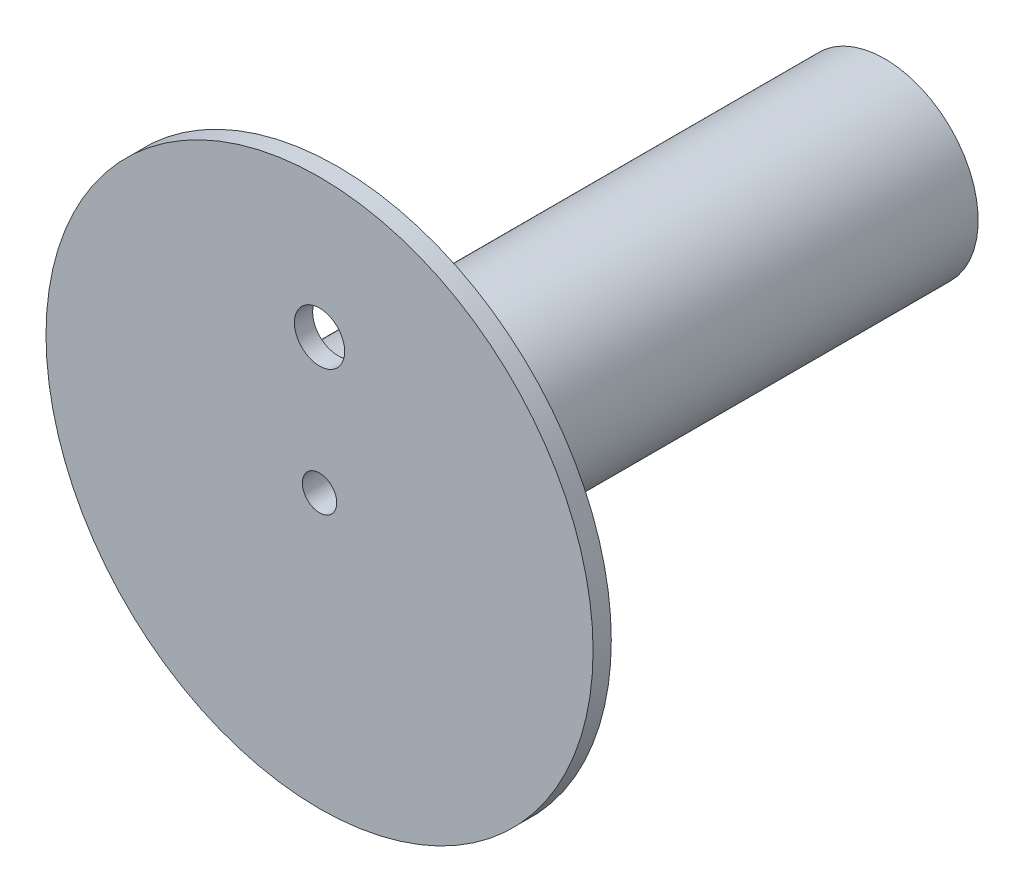
SolidWorks part; units mm, degrees
ref_plane "Front Plane" through (0, 0, 0) normal (0, 0, 1) x (1, 0, 0)
ref_plane "Top Plane" through (0, 0, 0) normal (0, 1, 0) x (1, 0, 0)
ref_plane "Right Plane" through (0, 0, 0) normal (1, 0, 0) x (0, 0, -1)
sketch "Sketch1" plane through (0, 0, 0) normal (0, 0, 1) x (1, 0, 0)
  circle A0 centre (0, 0) radius 6.5
  dimension "D1" = 13
extrude "Boss-Extrude1" add sketch "Sketch1" along normal blind 38.1
sketch "Sketch2" plane through (0, 0, 38.1) normal (0, 0, 1) x (1, 0, 0)
  circle A0 centre (0, 0) radius 19.05
  dimension "D1" = 38.1
extrude "Boss-Extrude2" add sketch "Sketch2" along normal blind 1.27
sketch "Sketch3" plane through (0, 0, 0) normal (0, 0, -1) x (-1, 0, 0)
  circle A0 centre (0, 0) radius 1.2
  dimension "D1" = 2.4
extrude "Cut-Extrude1" cut sketch "Sketch3" against normal through all
sketch "Sketch4" plane through (0, 0, 38.1) normal (0, 0, -1) x (-1, 0, 0)
  circle A0 centre (0, 9.398) radius 1.75
  circle A1 centre (0, 0) radius 19.05 construction
  dimension "D1" = 3.5
  dimension "D2" = 9.398
extrude "Cut-Extrude2" cut sketch "Sketch4" against normal blind 7.62
